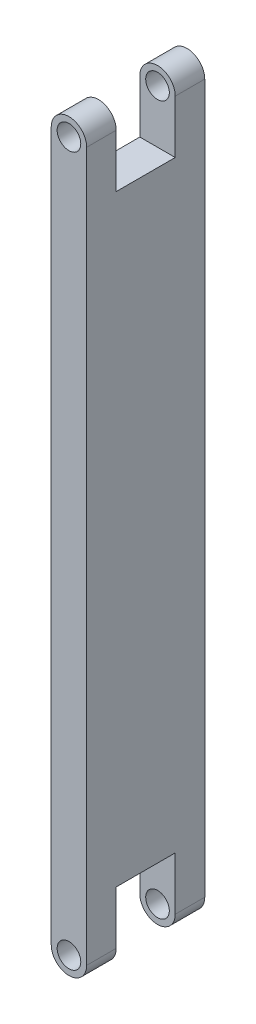
SolidWorks part; units mm, degrees
ref_plane "前视基准面" through (0, 0, 0) normal (0, 0, 1) x (1, 0, 0)
ref_plane "上视基准面" through (0, 0, 0) normal (0, 1, 0) x (1, 0, 0)
ref_plane "右视基准面" through (0, 0, 0) normal (1, 0, 0) x (0, 0, -1)
other "Configuration Table"
sketch "草图1" plane through (0, 0, 0) normal (0, 0, 1) x (1, 0, 0)
  line L0 (0, 0) -> (0, 300) construction
  line L1 (-7.5, 0) -> (-7.5, 300)
  line L2 (7.5, 0) -> (7.5, 300)
  arc A0 (-7.5, 0) -> (7.5, 0) centre (0, 0) ccw
  arc A1 (7.5, 300) -> (-7.5, 300) centre (0, 300) ccw
  point P3 (0, 150)
  dimension "D1" = 7.5
  dimension "D2" = 300
extrude "凸台-拉伸1" add sketch "草图1" along normal blind 50
sketch "草图2" plane through (7.5, 0, 0) normal (1, 0, 0) x (0, 0, -1)
  line L0 (0, 307.5) -> (-50, 307.5) construction
  line L1 (-37.5, 307.5) -> (-12.5, 307.5)
  line L2 (-37.5, 307.5) -> (-37.5, 277.5)
  line L3 (-37.5, 277.5) -> (-12.5, 277.5)
  line L4 (-12.5, 307.5) -> (-12.5, 277.5)
  line L5 (-50, -7.5) -> (0, -7.5) construction
  line L6 (-37.5, -7.5) -> (-12.5, -7.5)
  line L7 (-37.5, -7.5) -> (-37.5, 22.5)
  line L8 (-37.5, 22.5) -> (-12.5, 22.5)
  line L9 (-12.5, -7.5) -> (-12.5, 22.5)
  line L10 (0, 0) -> (0, 300) construction
  line L11 (-50, -7.5) -> (0, -7.5) construction
  dimension "D1" = 25
  dimension "D2" = 25
  dimension "D3" = 30
  dimension "D4" = 30
  dimension "D5" = 12.5
extrude "切除-拉伸1" cut sketch "草图2" against normal through all
sketch "草图3" plane through (0, 0, 50) normal (0, 0, 1) x (1, 0, 0)
  circle A0 centre (0, 300) radius 5
  circle A1 centre (0, 0) radius 5
  dimension "D1" = 10
extrude "切除-拉伸2" cut sketch "草图3" against normal through all
